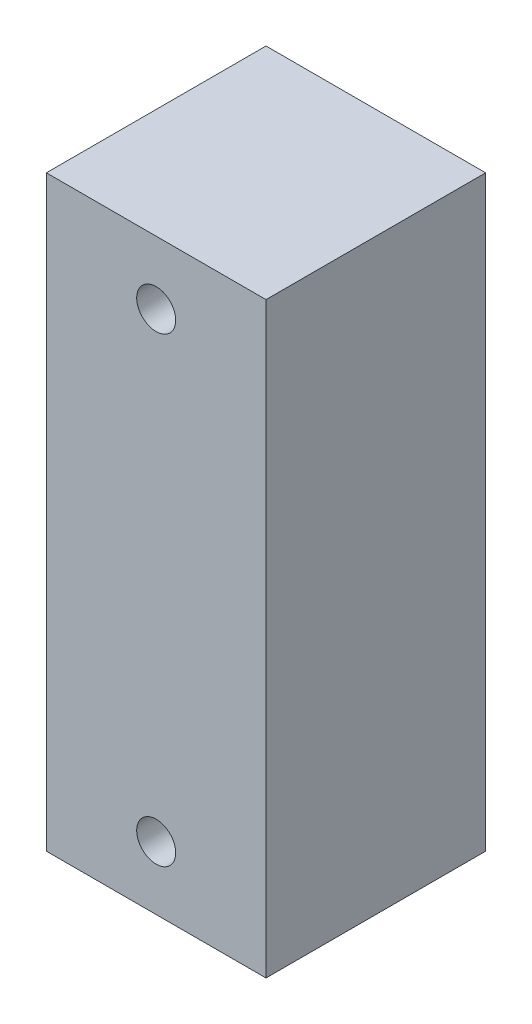
SolidWorks part; units mm, degrees
ref_plane "Ön Düzlem" through (0, 0, 0) normal (0, 0, 1) x (1, 0, 0)
ref_plane "Üst Düzlem" through (0, 0, 0) normal (0, 1, 0) x (1, 0, 0)
ref_plane "Sağ Düzlem" through (0, 0, 0) normal (1, 0, 0) x (0, 0, -1)
sketch "Çizim1" plane through (0, 0, 0) normal (0, 0, 1) x (1, 0, 0)
  line L1 (0, 0) -> (-20, 0)
  line L2 (0, 0) -> (0, -53.5)
  line L3 (0, -53.5) -> (-20, -53.5)
  line L4 (-20, 0) -> (-20, -53.5)
  dimension "D1" = 53.5
  dimension "D2" = 20
extrude "Yükseklik-Ekstrüzyon1" add sketch "Çizim1" along normal blind 20
sketch "Çizim2" plane through (0, 0, 20) normal (0, 0, 1) x (1, 0, 0)
  line L0 (-20, -53.5) -> (0, -53.5) construction
  circle A0 centre (-10, -5.75) radius 1.775
  circle A1 centre (-10, -47.75) radius 1.775
  dimension "D1" = 42
  dimension "D2" = 5.75
extrude "Kes-Ekstrüzyon1" cut sketch "Çizim2" against normal blind 59
